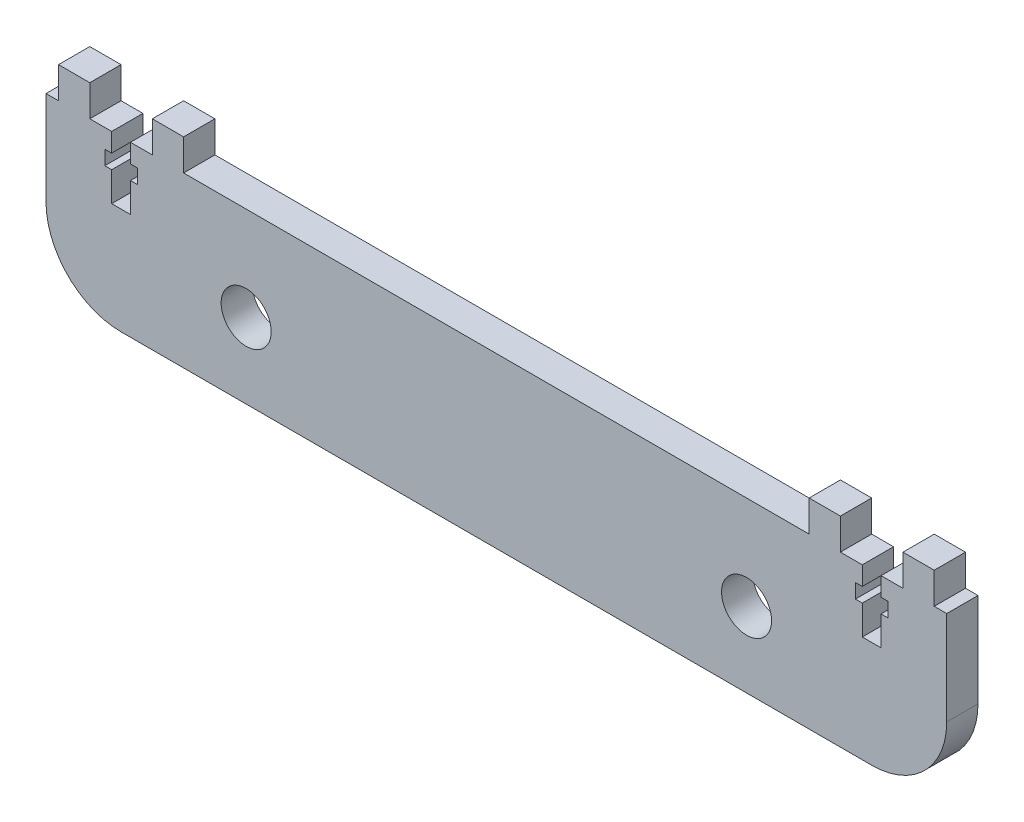
SolidWorks part; units mm, degrees
ref_plane "Front Plane" through (0, 0, 0) normal (0, 0, 1) x (1, 0, 0)
ref_plane "Top Plane" through (0, 0, 0) normal (0, 1, 0) x (1, 0, 0)
ref_plane "Right Plane" through (0, 0, 0) normal (1, 0, 0) x (0, 0, -1)
sketch "Sketch1" plane through (0, 0, 0) normal (0, 0, 1) x (1, 0, 0)
  line L0 (0, 0) -> (0, 77.1281) construction
  line L1 (0, 0) -> (-105.7988, 0) construction
  line L4 (-72, 0) -> (-72, 15)
  line L6 (-72, 15) -> (72, 15)
  line L7 (-60, -12) -> (60, -12)
  line L8 (72, 0) -> (72, 15)
  arc A1 (-72, 0) -> (-60, -12) centre (-60, 0) ccw
  circle A4 centre (-40, 0) radius 4
  circle A5 centre (40, 0) radius 4
  arc A6 (72, 0) -> (60, -12) centre (60, 0) cw
  point P12 (0, -12)
  point P13 (0, 15)
  point P14 (0, -12)
  point P15 (0, 15)
  line B0 (-57.4, 12) -> (-57.4, 9.7)
  line B1 (-61.5, 9.7) -> (-61.5, 5)
  line B2 (-58.5, 5) -> (-58.5, 9.7)
  line B3 (-57.4, 9.7) -> (-58.5, 9.7)
  line B4 (-60, 15) -> (-60, 3.7792) construction
  line B5 (-58.5, 15) -> (-55, 15)
  line B6 (-55, 20) -> (-50, 20)
  line B7 (-50, 20) -> (-50, 15)
  line B8 (-55, 20) -> (-55, 15)
  line B9 (-61.5, 15) -> (-65, 15)
  line B10 (-65, 15) -> (-65, 20)
  line B11 (-65, 20) -> (-70, 20)
  line B12 (-70, 20) -> (-70, 15)
  line B13 (-58.5, 15) -> (-61.5, 15) construction
  line B14 (-61.5, 15) -> (-61.5, 12)
  line B15 (-61.5, 9.7) -> (-62.6, 9.7)
  line B16 (-62.6, 12) -> (-61.5, 12)
  line B17 (-61.5, 5) -> (-58.5, 5)
  line B18 (-58.5, 12) -> (-57.4, 12)
  line B19 (-62.6, 9.7) -> (-62.6, 12)
  line B20 (-58.5, 12) -> (-58.5, 15)
  line B21 (-60, 5) -> (-60, 15) construction
  line B22 (57.4, 12) -> (57.4, 9.7)
  line B23 (61.5, 9.7) -> (61.5, 5)
  line B24 (58.5, 5) -> (58.5, 9.7)
  line B25 (57.4, 9.7) -> (58.5, 9.7)
  line B26 (60, 15) -> (60, 3.7792) construction
  line B27 (58.5, 15) -> (55, 15)
  line B28 (55, 20) -> (50, 20)
  line B29 (50, 20) -> (50, 15)
  line B30 (55, 20) -> (55, 15)
  line B31 (61.5, 15) -> (65, 15)
  line B32 (65, 15) -> (65, 20)
  line B33 (65, 20) -> (70, 20)
  line B34 (70, 20) -> (70, 15)
  line B35 (58.5, 15) -> (61.5, 15) construction
  line B36 (61.5, 15) -> (61.5, 12)
  line B37 (61.5, 9.7) -> (62.6, 9.7)
  line B38 (62.6, 12) -> (61.5, 12)
  line B39 (61.5, 5) -> (58.5, 5)
  line B40 (58.5, 12) -> (57.4, 12)
  line B41 (62.6, 9.7) -> (62.6, 12)
  line B42 (58.5, 12) -> (58.5, 15)
  line B43 (60, 5) -> (60, 15) construction
  dimension "D3" = 12
  dimension "D4" = 12
  dimension "D6" = 8
  dimension "D1" = 60
  dimension "D2" = 40
  dimension "D5" = 15
sketch_block_instance "Insert M3 plots ep 5mm-1"
sketch_block "Insert M3 plots ep 5mm" parameters "D1"=10, "D2"=5, "D3"=5
sketch_block_instance "Decoupe Insert M3-4"
sketch_block "Decoupe Insert M3" parameters "D1"=5.2, "D2"=3, "D3"=2.3, "D4"=3, "D5"=10
sketch_block_instance "Insert M3 plots ep 5mm-4"
extrude "Boss-Extrude2" add sketch "Sketch1" along normal blind 5 contours B40 B42 L6 B20 B18 B0 B3 B2 B17 B1 B15 B19 B16 B14 L4 A1 L7 A6 L8 B36 B38 B41 B37 B23 B39 B24 B25 B22 A4 A5 | B30 B28 B29 L6 | B34 B33 B32 L6 | B11 B12 L6 B10 | B6 B8 L6 B7
